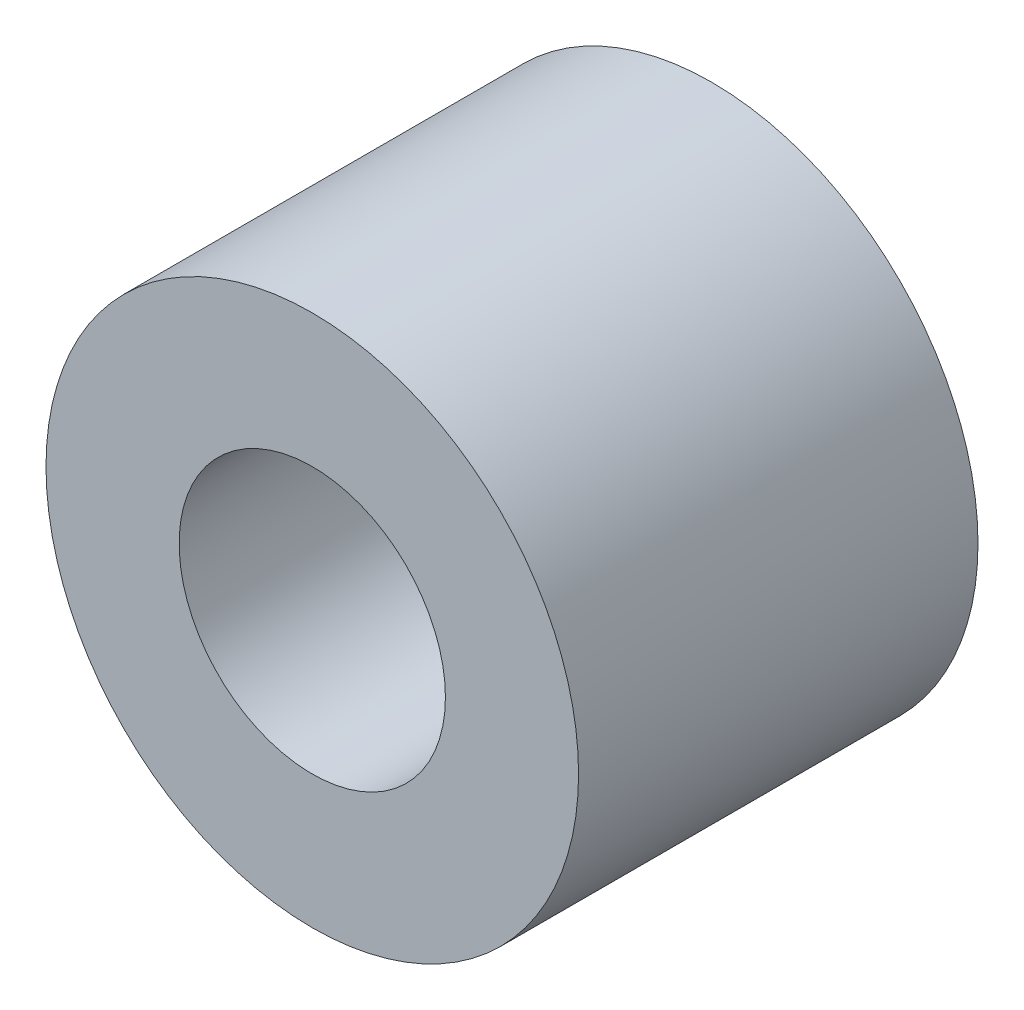
SolidWorks part; units mm, degrees
ref_plane "前视基准面" through (0, 0, 0) normal (0, 0, 1) x (1, 0, 0)
ref_plane "上视基准面" through (0, 0, 0) normal (0, 1, 0) x (1, 0, 0)
ref_plane "右视基准面" through (0, 0, 0) normal (1, 0, 0) x (0, 0, -1)
other "Configuration Table"
sketch "草图1" plane through (0, 0, 0) normal (0, 0, 1) x (1, 0, 0)
  circle A0 centre (0, 0) radius 4
  circle A1 centre (0, 0) radius 2
extrude "参考外形_非实物型号" add sketch "草图1" along normal blind 6
